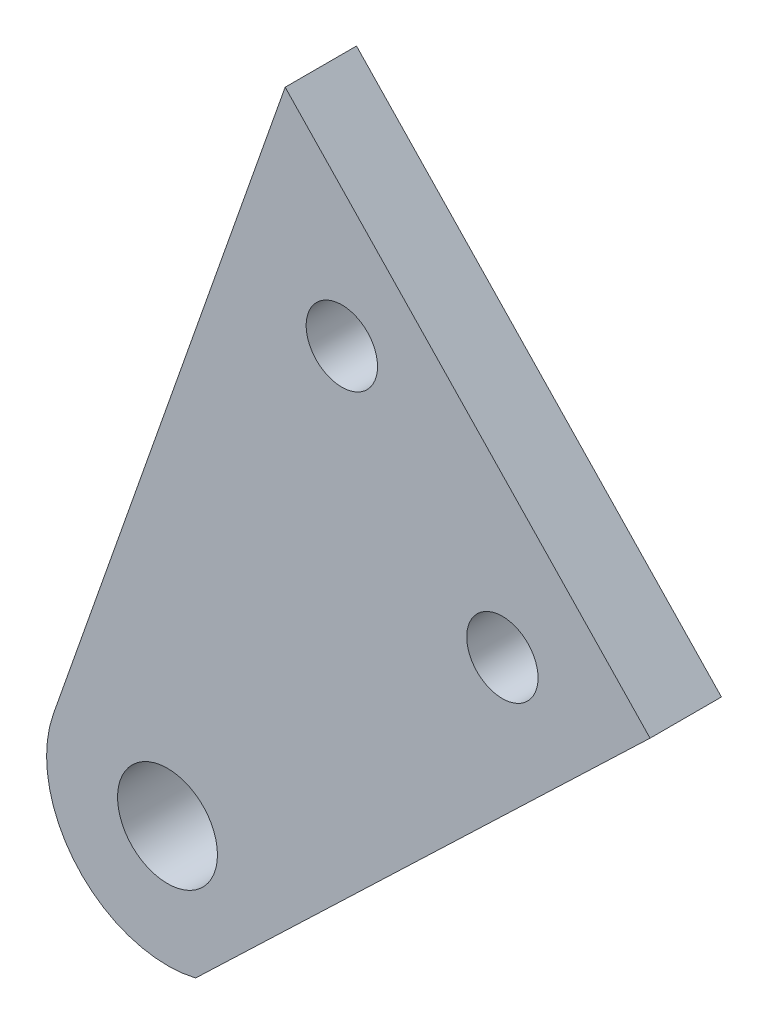
SolidWorks part; units mm, degrees
ref_plane "Front Plane" through (0, 0, 0) normal (0, 0, 1) x (1, 0, 0)
ref_plane "Top Plane" through (0, 0, 0) normal (0, 1, 0) x (1, 0, 0)
ref_plane "Right Plane" through (0, 0, 0) normal (1, 0, 0) x (0, 0, -1)
sketch "Sketch1" plane through (0, 0, 0) normal (0, 0, 1) x (1, 0, 0)
  line L0 (-23.8468, 12.3156) -> (-25.791, 1.5884)
  line L1 (-18.5875, -2.4087) -> (-9.5549, 5.7877)
  line L2 (-23.8468, 12.3156) -> (-22.0455, 21.7722)
  line L3 (-21.4374, 24.9647) -> (-6.0923, 8.9297)
  line L4 (-6.0923, 8.9297) -> (-9.5549, 5.7877)
  line L5 (-21.4374, 24.9647) -> (-22.0455, 21.7722)
  arc A0 (-25.791, 1.5884) -> (-18.5875, -2.4087) centre (-21.5107, 0.8127) ccw
  circle A1 centre (-19.054, 16.7309) radius 1.5
  circle A2 centre (-12.3033, 8.7654) radius 1.5
extrude "Boss-Extrude1" add sketch "Sketch1" along normal blind 3
sketch "Sketch3" plane through (0, 0, 3) normal (0, 0, 1) x (1, 0, 0)
  circle A0 centre (-21.5127, 0.8097) radius 2.1
  dimension "D3" = 4.2
extrude "Cut-Extrude1" cut sketch "Sketch3" against normal blind 5
sketch "Sketch4" plane through (0, 0, 3) normal (0, 0, 1) x (1, 0, 0)
  line L0 (-21.4374, 24.9647) -> (-6.0923, 8.9297)
  line L1 (-6.0923, 8.9297) -> (-25.2038, -9.3595)
  line L2 (-21.4374, 24.9647) -> (-31.1816, -2.7256)
  arc A0 (-31.1816, -2.7256) -> (-25.2038, -9.3595) centre (-26.3849, -4.4135) ccw
  circle A1 centre (-26.3849, -4.4135) radius 2.1
  circle A2 centre (-12.3033, 8.7654) radius 1.5
  circle A3 centre (-19.054, 16.7309) radius 1.5
  dimension "D1" = 4.2
extrude "Boss-Extrude2" add sketch "Sketch4" against normal blind 3
